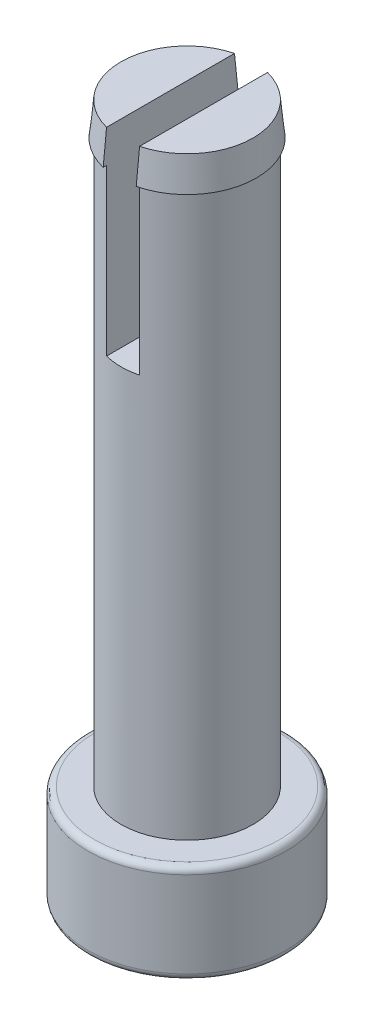
SolidWorks part; units mm, degrees
ref_plane "前视基准面" through (0, 0, 0) normal (0, 0, 1) x (1, 0, 0)
ref_plane "上视基准面" through (0, 0, 0) normal (0, 1, 0) x (1, 0, 0)
ref_plane "右视基准面" through (0, 0, 0) normal (1, 0, 0) x (0, 0, -1)
sketch "草图1" plane through (0, 0, 0) normal (0, 1, 0) x (1, 0, 0)
  circle A0 centre (0, 0) radius 3
  dimension "D1" = 6
extrude "凸台-拉伸1" add sketch "草图1" along normal blind 3
sketch "草图2" plane through (0, 3, 0) normal (0, 1, 0) x (1, 0, 0)
  circle A0 centre (0, 0) radius 2
  dimension "D1" = 4
extrude "凸台-拉伸2" add sketch "草图2" along normal blind 18
sketch "草图3" plane through (0, 0, 0) normal (0, 0, 1) x (1, 0, 0)
  line L0 (0, 21) -> (-2, 21)
  line L1 (2, 21) -> (-2, 21) construction
  line L2 (-2, 21) -> (-2.1, 20)
  line L3 (-2.1, 20) -> (0, 20)
  line L4 (0, 20) -> (0, 21)
  dimension "D1" = 1
  dimension "D2" = 2.1
revolve "旋转1" add sketch "草图3" angle 360 about L4
sketch "草图4" plane through (0, 21, 0) normal (0, 1, 0) x (1, 0, 0)
  line L0 (0.5, 2.4688) -> (-0.5, 2.4688)
  line L1 (0.5, 2.4688) -> (0.5, -2.4688)
  line L2 (-0.5, 2.4688) -> (-0.5, -2.4688)
  line L3 (0.5, -2.4688) -> (-0.5, -2.4688)
  line L4 (0.5, 2.4688) -> (-0.5, -2.4688) construction
  line L5 (-0.5, 2.4688) -> (0.5, -2.4688) construction
  point P1 (0, 0)
  dimension "D1" = 1
extrude "切除-拉伸1" cut sketch "草图4" against normal blind 6
fillet "圆角1" radius 0.2 2 edges at (0, 3, 3) (0, 0, 3)
